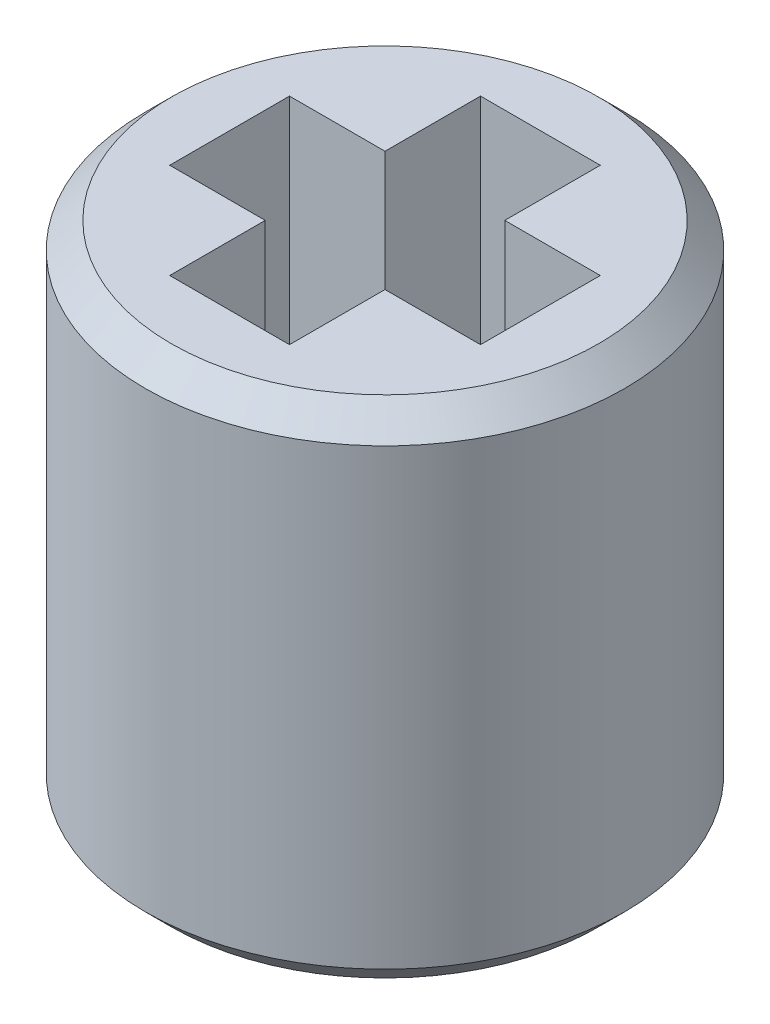
SolidWorks part; units mm, degrees
ref_plane "Front Plane" through (0, 0, 0) normal (0, 0, 1) x (1, 0, 0)
ref_plane "Top Plane" through (0, 0, 0) normal (0, 1, 0) x (1, 0, 0)
ref_plane "Right Plane" through (0, 0, 0) normal (1, 0, 0) x (0, 0, -1)
sketch "Sketch1" plane through (0, 0, 0) normal (0, 1, 0) x (1, 0, 0)
  circle A0 centre (0, 0) radius 3.7
  dimension "D1" = 7.4
extrude "Boss-Extrude1" add sketch "Sketch1" along normal mid plane 7.8
sketch "Sketch2" plane through (0, 3.9, 0) normal (0, 1, 0) x (1, 0, 0)
  line L0 (0.925, 0.925) -> (2.4, 0.925)
  line L1 (-2.4, 0.925) -> (-0.925, 0.925)
  line L2 (-2.4, 0.925) -> (-2.4, -0.925)
  line L3 (-2.4, -0.925) -> (-0.925, -0.925)
  line L4 (2.4, 0.925) -> (2.4, -0.925)
  line L5 (-2.4, 0.925) -> (2.4, -0.925) construction
  line L6 (-2.4, -0.925) -> (2.4, 0.925) construction
  line L7 (-0.925, 2.4) -> (0.925, 2.4)
  line L8 (-0.925, 2.4) -> (-0.925, 0.925)
  line L9 (-0.925, -2.4) -> (0.925, -2.4)
  line L10 (0.925, 2.4) -> (0.925, 0.925)
  line L11 (-0.925, 2.4) -> (0.925, -2.4) construction
  line L12 (-0.925, -2.4) -> (0.925, 2.4) construction
  line L13 (0.925, -0.925) -> (2.4, -0.925)
  line L14 (-0.925, -0.925) -> (-0.925, -2.4)
  line L15 (0.925, -0.925) -> (0.925, -2.4)
  point P0 (0, 0)
  point P6 (0, 0)
  dimension "D1" = 1.85
  dimension "D2" = 1.85
  dimension "D3" = 4.8
  dimension "D4" = 4.8
extrude "Cut-Extrude1" cut sketch "Sketch2" against normal through all
chamfer "Chamfer1" distance 0.4 angle 45 2 edges at (0, -3.9, 3.7) (0, 3.9, 3.7)
